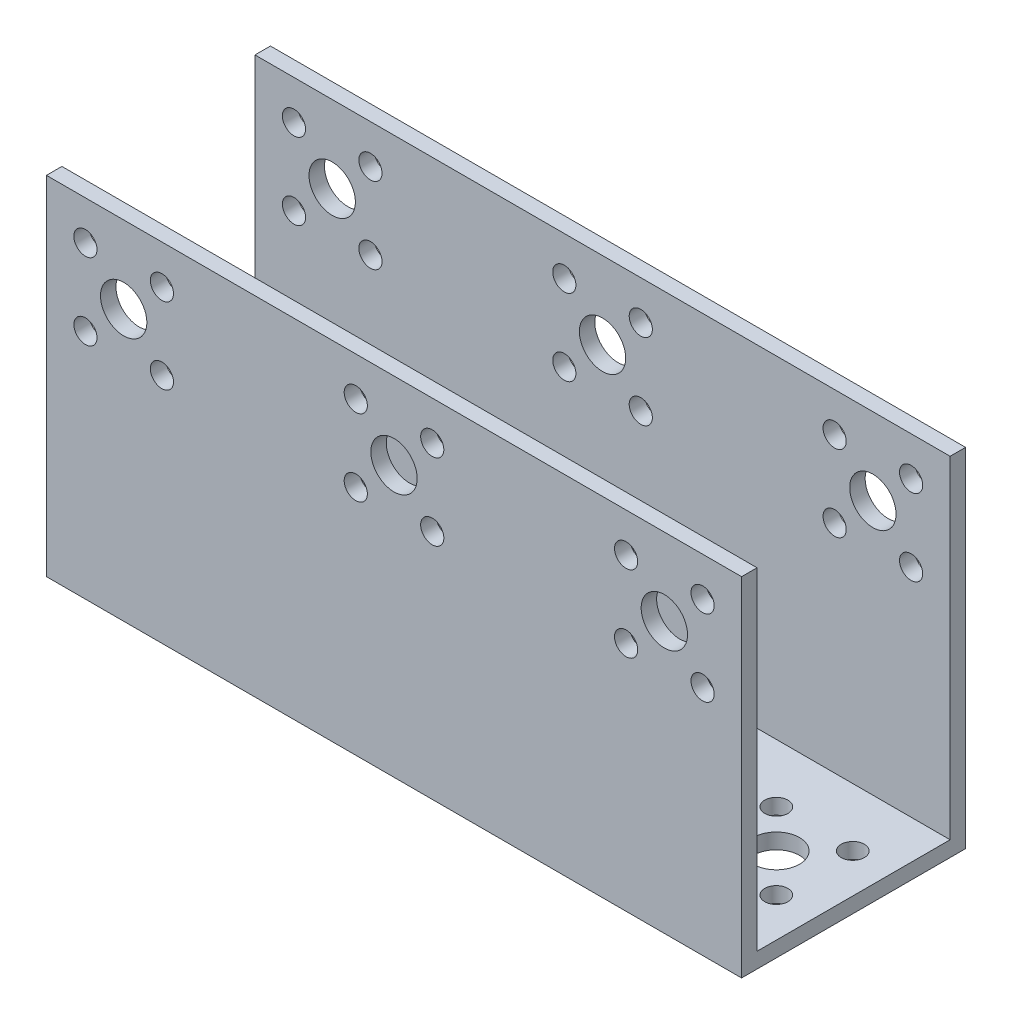
SolidWorks part; units mm, degrees
ref_plane "前视基准面" through (0, 0, 0) normal (0, 0, 1) x (1, 0, 0)
ref_plane "上视基准面" through (0, 0, 0) normal (0, 1, 0) x (1, 0, 0)
ref_plane "右视基准面" through (0, 0, 0) normal (1, 0, 0) x (0, 0, -1)
sketch "草图1" plane through (0, 0, 0) normal (0, 1, 0) x (1, 0, 0)
  line L1 (0, 0) -> (90, 0)
  line L2 (0, 0) -> (0, 29)
  line L3 (0, 29) -> (90, 29)
  line L4 (90, 0) -> (90, 29)
  dimension "D1" = 29
  dimension "D2" = 90
extrude "凸台-拉伸1" add sketch "草图1" along normal blind 2
sketch "草图4" plane through (0, 2, 0) normal (0, 1, 0) x (1, 0, 0)
  line L0 (0, 14.5) -> (90, 14.5) construction
  line L1 (0, 29) -> (0, 0) construction
  line L2 (90, 0) -> (90, 29) construction
  line L3 (45, 29) -> (45, 0) construction
  line L4 (90, 29) -> (0, 29) construction
  line L5 (80, 29) -> (80, 0) construction
  line L6 (0, 0) -> (90, 0) construction
  line L7 (10, 29) -> (10, 0) construction
  circle A0 centre (45, 14.5) radius 3
  circle A1 centre (45, 14.5) radius 7.5671 construction
  circle A2 centre (54.9, 14.5) radius 7.5671 construction
  circle A3 centre (49.95, 20.2235) radius 1.5
  circle A4 centre (49.9495, 10.324) radius 1.5
  circle A5 centre (40.05, 10.3245) radius 1.5
  circle A6 centre (40.0505, 20.224) radius 1.5
  circle A7 centre (80, 14.5) radius 3
  circle A8 centre (84.95, 19.4495) radius 1.5
  circle A9 centre (75.0505, 19.45) radius 1.5
  circle A10 centre (75.05, 9.5505) radius 1.5
  circle A11 centre (84.9495, 9.55) radius 1.5
  circle A12 centre (5.0505, 9.55) radius 1.5
  circle A13 centre (14.95, 9.5505) radius 1.5
  circle A14 centre (5.05, 19.4495) radius 1.5
  circle A15 centre (10, 14.5) radius 3
  circle A16 centre (14.9495, 19.45) radius 1.5
  point P26 (45, 15.274)
  dimension "D1" = 9.9
  dimension "D2" = 4
  dimension "D3" = 35
  dimension "D4" = 14.5
extrude "切除-拉伸1" cut sketch "草图4" against normal blind 2
sketch "草图2" plane through (0, 2, 0) normal (0, 1, 0) x (1, 0, 0)
  line L1 (0, 29) -> (90, 29)
  line L2 (0, 29) -> (0, 27)
  line L3 (0, 27) -> (90, 27)
  line L4 (90, 29) -> (90, 27)
  dimension "D1" = 2
extrude "凸台-拉伸2" add sketch "草图2" along normal blind 43
sketch "草图5" plane through (0, 0, -27) normal (0, 0, 1) x (1, 0, 0)
  line L0 (0, 35) -> (90, 35) construction
  line L1 (0, 45) -> (0, 2) construction
  line L2 (90, 45) -> (90, 2) construction
  line L3 (45, 45) -> (45, 2) construction
  line L4 (0, 45) -> (90, 45) construction
  line L5 (0, 2) -> (90, 2) construction
  line L6 (0, 35) -> (90, 35) construction
  line L7 (45, 48.726) -> (45, 19.726) construction
  line L8 (80, 48.726) -> (80, 19.726) construction
  line L9 (10, 48.726) -> (10, 19.726) construction
  circle A0 centre (45, 35) radius 3
  circle A1 centre (45, 35) radius 7 construction
  circle A2 centre (54.9, 35) radius 7 construction
  circle A3 centre (49.95, 39.9495) radius 1.5
  circle A4 centre (49.9495, 30.05) radius 1.5
  circle A5 centre (40.05, 30.0505) radius 1.5
  circle A6 centre (40.0505, 39.95) radius 1.5
  circle A7 centre (80, 35) radius 3
  circle A8 centre (84.95, 39.9495) radius 1.5
  circle A9 centre (75.0505, 39.95) radius 1.5
  circle A10 centre (75.05, 30.0505) radius 1.5
  circle A11 centre (84.9495, 30.05) radius 1.5
  circle A12 centre (5.0505, 30.05) radius 1.5
  circle A13 centre (14.95, 30.0505) radius 1.5
  circle A14 centre (5.05, 39.9495) radius 1.5
  circle A15 centre (10, 35) radius 3
  circle A16 centre (14.9495, 39.95) radius 1.5
  point P31 (45, 35)
  dimension "D1" = 10
  dimension "D2" = 9.9
  dimension "D3" = 35
extrude "切除-拉伸2" cut sketch "草图5" against normal blind 2
ref_plane "基准面1" through (0, 0, -14.5) normal (0, 0, -1) x (-1, 0, 0)
mirror "镜向1" about plane through (0, 0, -14.5) normal (0, 0, -1) of "凸台-拉伸2", "切除-拉伸2"
